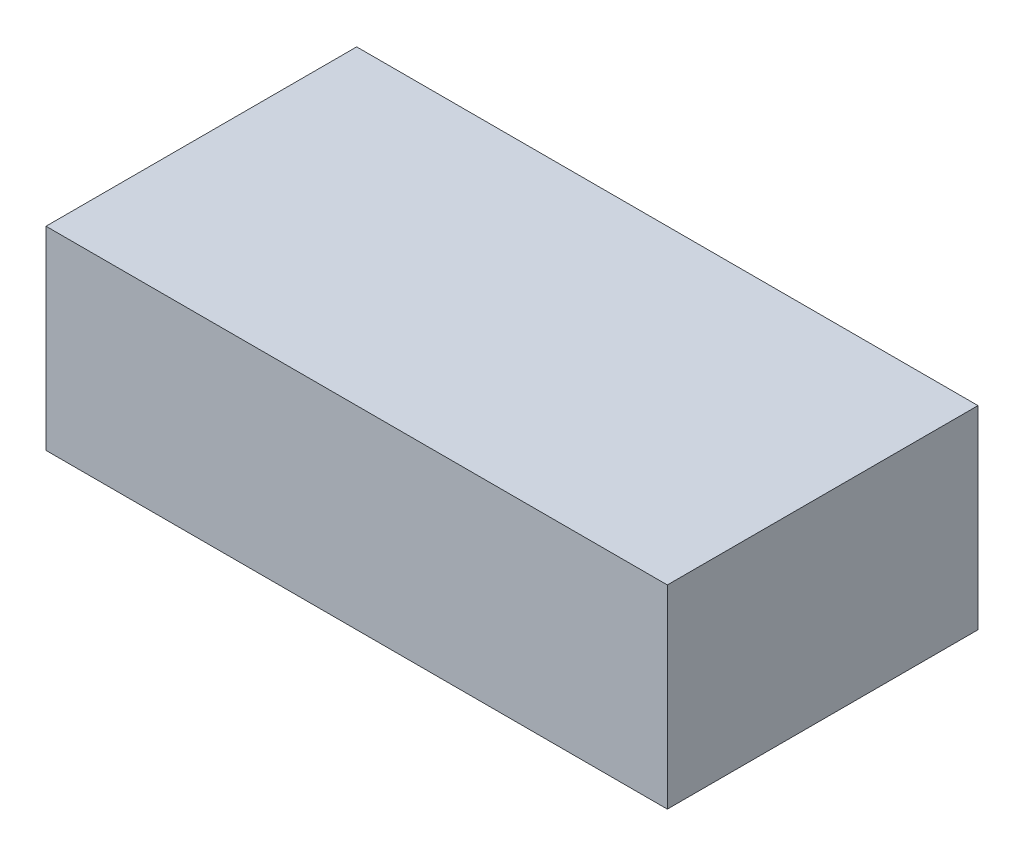
SolidWorks part; units mm, degrees
material "Malleable Cast Iron"
ref_plane "Front Plane" through (0, 0, 0) normal (0, 0, 1) x (1, 0, 0)
ref_plane "Top Plane" through (0, 0, 0) normal (0, 1, 0) x (1, 0, 0)
ref_plane "Right Plane" through (0, 0, 0) normal (1, 0, 0) x (0, 0, -1)
sketch "Sketch1" plane through (0, 0, 0) normal (0, 1, 0) x (1, 0, 0)
  line L1 (0, 0) -> (101.6, 0)
  line L2 (0, 0) -> (0, 50.8)
  line L3 (0, 50.8) -> (101.6, 50.8)
  line L4 (101.6, 0) -> (101.6, 50.8)
  dimension "D1" = 101.6
  dimension "D2" = 50.8
extrude "Boss-Extrude1" add sketch "Sketch1" along normal blind 31.75
